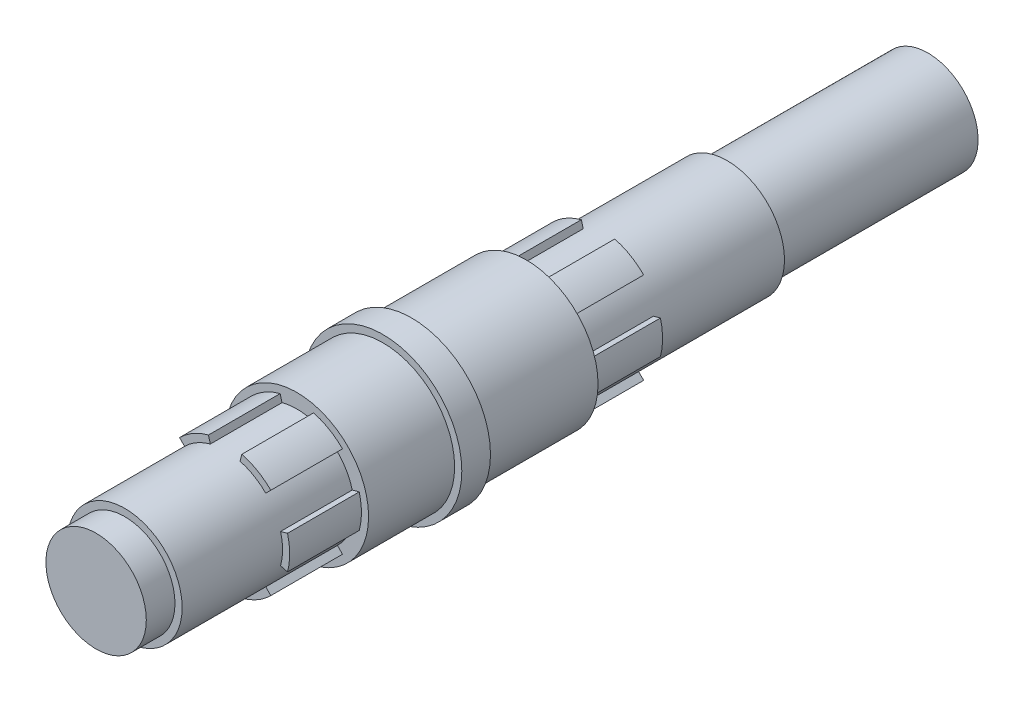
SolidWorks part; units mm, degrees
ref_plane "Front Plane" through (0, 0, 0) normal (0, 0, 1) x (1, 0, 0)
ref_plane "Top Plane" through (0, 0, 0) normal (0, 1, 0) x (1, 0, 0)
ref_plane "Right Plane" through (0, 0, 0) normal (1, 0, 0) x (0, 0, -1)
sketch "Sketch3" plane through (0, 0, 0) normal (1, 0, 0) x (0, 0, -1)
  line L0 (-146.05, 0) -> (-146.05, 25.4)
  line L1 (-146.05, 25.4) -> (-88.9, 25.4)
  line L2 (-128.2791, 0) -> (133.2129, 0) construction
  line L3 (-88.9, 25.4) -> (-88.9, 28.575)
  line L4 (-88.9, 28.575) -> (-57.15, 28.575)
  line L5 (-57.15, 28.575) -> (-57.15, 31.75)
  line L6 (-57.15, 31.75) -> (44.45, 31.75)
  line L7 (44.45, 31.75) -> (44.45, 28.575)
  line L8 (44.45, 28.575) -> (76.2, 28.575)
  line L9 (76.2, 28.575) -> (76.2, 25.4)
  line L10 (76.2, 25.4) -> (146.05, 25.4)
  line L11 (146.05, 25.4) -> (146.05, 0)
  line L12 (-146.05, 0) -> (146.05, 0)
  dimension "D1" = 25.4
  dimension "D2" = 57.15
  dimension "D3" = 146.05
  dimension "D4" = 3.175
  dimension "D5" = 31.75
  dimension "D6" = 3.175
  dimension "D7" = 101.6
  dimension "D8" = 69.85
revolve "Revolve1" add sketch "Sketch3" angle 360 about L2
sketch "Sketch5" plane through (0, 0, 88.9) normal (0, 0, 1) x (1, 0, 0)
  line L0 (0, 0) -> (0, 28.575)
  line L1 (0, 0) -> (9.319, 34.7791)
  line L2 (0, 0) -> (-9.2996, 34.7067)
  circle A0 centre (0, 0) radius 28.575 construction
  circle M4 centre (0, 0) radius 25.4
  circle M5 centre (0, 0) radius 28.575
  dimension "D1" = 15
  dimension "D2" = 15
extrude "Cut-Extrude2" cut sketch "Sketch5" against normal blind 31.75 contours L1 L0 M4 M5 | L2 L0 M4 M5
pattern_circular "CirPattern1" count 6 over 360 about axis through (0, 0, 0) along (0, 0, 1) of "Cut-Extrude2"
sketch "Sketch6" plane through (0, 0, -76.2) normal (0, 0, -1) x (-1, 0, 0)
  line L0 (0, 0) -> (0, 40.5155)
  line L1 (0, 0) -> (10.6125, 39.6063)
  line L2 (0, 0) -> (-10.6721, 39.8289)
  circle M4 centre (0, 0) radius 28.575
  circle M5 centre (0, 0) radius 25.4
  dimension "D1" = 15
  dimension "D2" = 15
extrude "Cut-Extrude3" cut sketch "Sketch6" against normal blind 31.75 contours L1 L0 M5 M4 | L2 L0 M5 M4
pattern_circular "CirPattern2" count 6 over 360 about axis through (0, 0, 0) along (0, 0, 1) of "Cut-Extrude3"
sketch "Sketch7" plane through (0, 0, 146.05) normal (0, 0, 1) x (1, 0, 0)
  circle A0 centre (0, 0) radius 22.225
  circle A1 centre (0, 0) radius 25.4
  dimension "D1" = 44.45
extrude "Cut-Extrude4" cut sketch "Sketch7" against normal blind 12.7
sketch "Sketch8" plane through (0, 0, -146.05) normal (0, 0, -1) x (-1, 0, 0)
  circle A0 centre (0, 0) radius 25.4
  circle A1 centre (0, 0) radius 22.225
  dimension "D1" = 44.45
extrude "Cut-Extrude5" cut sketch "Sketch8" against normal blind 12.7
sketch "Sketch9" plane through (0, 0, 57.15) normal (0, 0, 1) x (1, 0, 0)
  circle A0 centre (0, 0) radius 34.925
extrude "Boss-Extrude1" add sketch "Sketch9" against normal blind 12.7 from offset 38.1 offset against normal yes
sketch "Sketch10" plane through (0, 0, -146.05) normal (0, 0, -1) x (-1, 0, 0)
  circle A0 centre (0, 0) radius 22.225
extrude "Boss-Extrude2" add sketch "Sketch10" along normal blind 76.2
